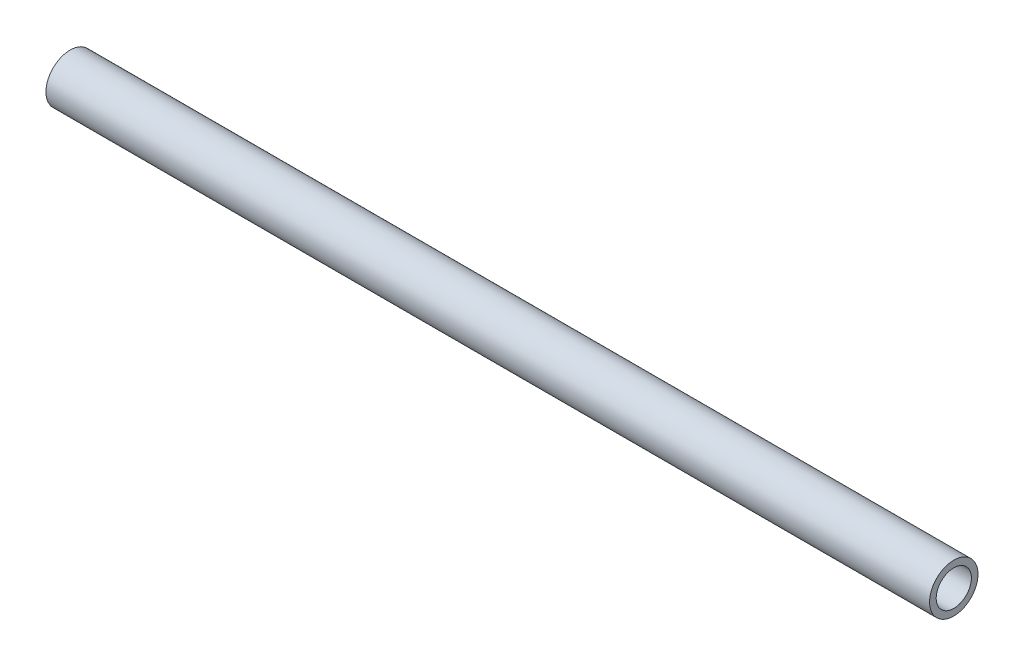
SolidWorks part; units mm, degrees
ref_plane "Front Plane" through (0, 0, 0) normal (0, 0, 1) x (1, 0, 0)
ref_plane "Top Plane" through (0, 0, 0) normal (0, 1, 0) x (1, 0, 0)
ref_plane "Right Plane" through (0, 0, 0) normal (1, 0, 0) x (0, 0, -1)
sketch "Sketch1" plane through (0, 0, 0) normal (1, 0, 0) x (0, 0, -1)
  circle A0 centre (0, 0) radius 13.15
  circle A1 centre (0, 0) radius 9.55
  dimension "D1" = 26.3
  dimension "D2" = 19.1
extrude "Boss-Extrude1" add sketch "Sketch1" along normal blind 480
